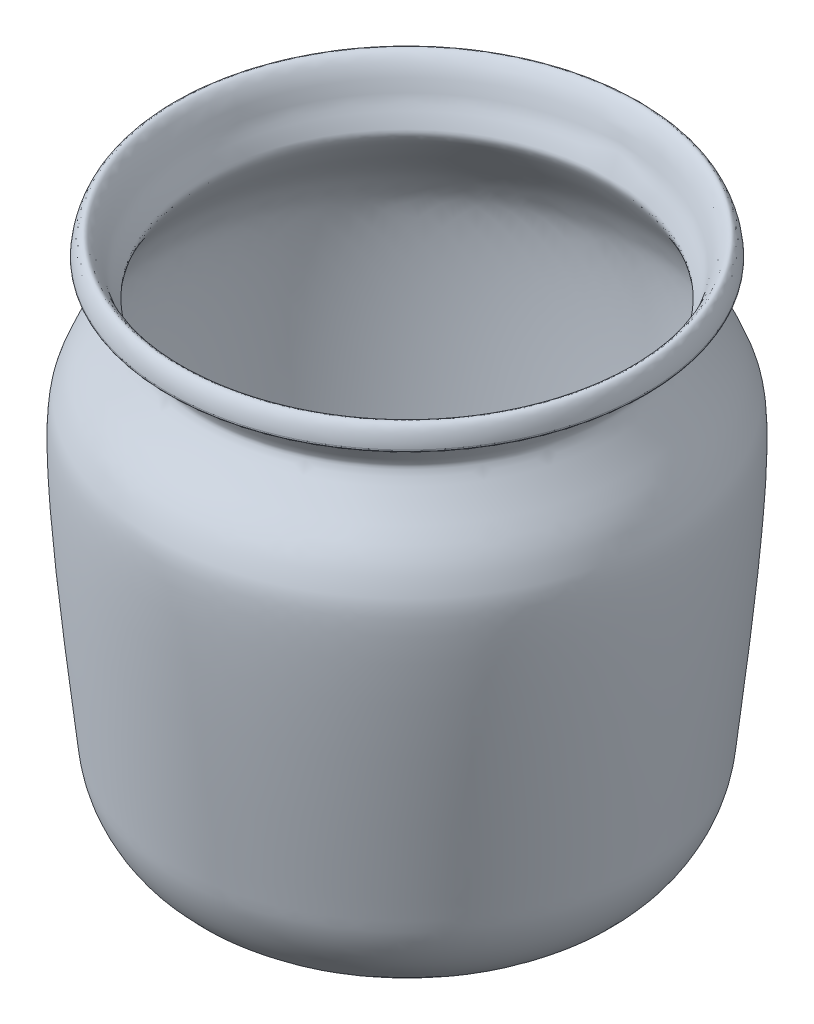
SolidWorks part; units mm, degrees
material "AISI 304"
ref_plane "Front Plane" through (0, 0, 0) normal (0, 0, 1) x (1, 0, 0)
ref_plane "Top Plane" through (0, 0, 0) normal (0, 1, 0) x (1, 0, 0)
ref_plane "Right Plane" through (0, 0, 0) normal (1, 0, 0) x (0, 0, -1)
sketch "Sketch1" plane through (0, 0, 0) normal (0, 0, 1) x (1, 0, 0)
  line L0 (0, -86.8581) -> (0, 83.1376) construction
  line L1 (0, 10.6322) -> (115.3338, 10.6322) construction
  line L2 (0, 10.6322) -> (0, 544.0322)
  line L3 (0, 544.0322) -> (249.5505, 544.0322)
  line L4 (249.5505, 544.0322) -> (249.5505, 493.2322)
  line L5 (249.5505, 493.2322) -> (222.25, 493.2322)
  spline S0 degree 3 poles (0, 10.6322) (91.2801, 10.6322) (93.72, 10.7307) (110.2027, 10.5039) (147.0297, 13.8652) (199.0837, 43.4573) (217.3574, 78.9219) (221.4091, 124.4615) (247.8714, 352.6167) (232.5198, 391.8029) (224.6314, 412.0028) (190.7903, 455.0657) (194.5088, 467.3938) (202.8123, 482.4004) (204.6795, 496.5386) (213.0492, 511.6609) (218.9085, 510.5092) (222.4459, 499.5721) (222.25, 493.2322) knots 0 0 0 0 0.148265 0.184499 0.34258 0.376883 0.493226 0.520597 0.623222 0.639919 0.674745 0.738436 0.754449 0.83487 0.871422 0.92814 0.940998 1 1 1 1
  dimension "D1" = 215.9
  dimension "D2" = 222.25
  dimension "D3" = 533.4
  dimension "D4" = 500.38
  dimension "D5" = 482.6
  dimension "D6" = 485.14
  dimension "D7" = 474.98
  dimension "D8" = 449.58
  dimension "D9" = 398.78
  dimension "D10" = 373.38
  dimension "D11" = 93.98
  dimension "D12" = 219.6338
  dimension "D13" = 101.6
  dimension "D14" = 177.8
  dimension "D15" = 235.5494
  dimension "D16" = 192.5777
revolve "Revolve1" add sketch "Sketch1" angle 360 about L2
shell "Shell1" thickness 2
sketch "Sketch2" plane through (0, 0, 0) normal (0, 0, 1) x (1, 0, 0)
  line L0 (-224.2284, 495.2322) -> (-224.486, 490.3821)
  line L3 (247.5505, 495.2322) -> (-247.5505, 495.2322) construction
  line L4 (224.2206, 495.2322) -> (-224.2206, 495.2322) construction
  line L5 (-224.486, 490.3821) -> (-251.2108, 480.9372)
  line L6 (-251.2108, 480.9372) -> (-258.083, 518.8199)
  line L7 (-258.083, 518.8199) -> (-258.083, 570.5956)
  line L8 (-258.083, 570.5956) -> (-222.9759, 558.3114)
  line L9 (-222.9759, 558.3114) -> (-224.9002, 515.06)
  line L10 (-224.9002, 515.06) -> (-224.9002, 503.2657)
  line L11 (-224.9002, 503.2657) -> (-224.2284, 495.2322)
  line L12 (0, 588.7155) -> (0, 415.3772) construction
revolve "Cut-Revolve1" cut sketch "Sketch2" angle 360 about L12
sketch "Sketch3" plane through (0, 0, 0) normal (0, 1, 0) x (1, 0, 0)
  circle A0 centre (0, 0) radius 76.2
  dimension "D1" = 152.4
extrude "Cut-Extrude1" cut sketch "Sketch3" along normal up to next
fillet "Fillet1" radius 0.762 2 edges at (0, 493.2322, -224.3347) (0, 493.2322, -222.25)
sketch "Sketch4" plane through (0, 0, 0) normal (0, 1, 0) x (1, 0, 0)
  line L0 (0, 0) -> (294.251, 0) construction
  line L1 (0, 0) -> (0, 152.2365) construction
  circle A1 centre (101.6, -11) radius 11
  dimension "D1" = 22
  dimension "D2" = 101.6
extrude "Cut-Extrude2" cut sketch "Sketch4" along normal up to next and the other way through all
pattern_circular "CirPattern8" count 9 over 360 about axis through (0, 0, 0) along (0, 1, 0) of "Cut-Extrude2"
